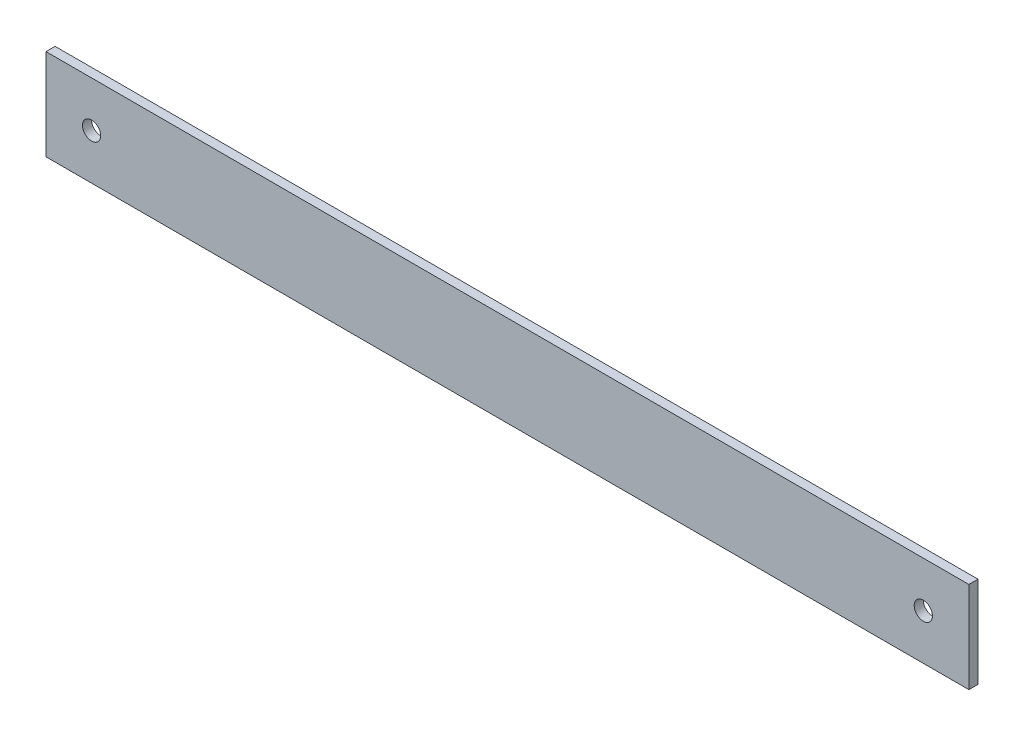
SolidWorks part; units mm, degrees
ref_plane "Front Plane" through (0, 0, 0) normal (0, 0, 1) x (1, 0, 0)
ref_plane "Top Plane" through (0, 0, 0) normal (0, 1, 0) x (1, 0, 0)
ref_plane "Right Plane" through (0, 0, 0) normal (1, 0, 0) x (0, 0, -1)
sketch "Sketch1" plane through (0, 0, 0) normal (0, 0, 1) x (1, 0, 0)
  line L1 (-101.275, 10) -> (101.275, 10)
  line L2 (-101.275, 10) -> (-101.275, -10)
  line L3 (-101.275, -10) -> (101.275, -10)
  line L4 (101.275, 10) -> (101.275, -10)
  line L5 (-101.275, 10) -> (101.275, -10) construction
  line L6 (-101.275, -10) -> (101.275, 10) construction
  point P0 (0, 0)
  dimension "D1" = 20
  dimension "D2" = 202.55
extrude "Boss-Extrude1" add sketch "Sketch1" along normal blind 2
sketch "Sketch2" plane through (0, 0, 2) normal (0, 0, 1) x (1, 0, 0)
  line L0 (-101.275, 10) -> (-101.275, -10) construction
  line L1 (101.275, -10) -> (101.275, 10) construction
  circle A0 centre (-91.275, 0) radius 2
  circle A1 centre (91.275, 0) radius 2
  dimension "D1" = 4
  dimension "D2" = 4
  dimension "D3" = 10
  dimension "D4" = 10
extrude "Cut-Extrude1" cut sketch "Sketch2" against normal blind 2
